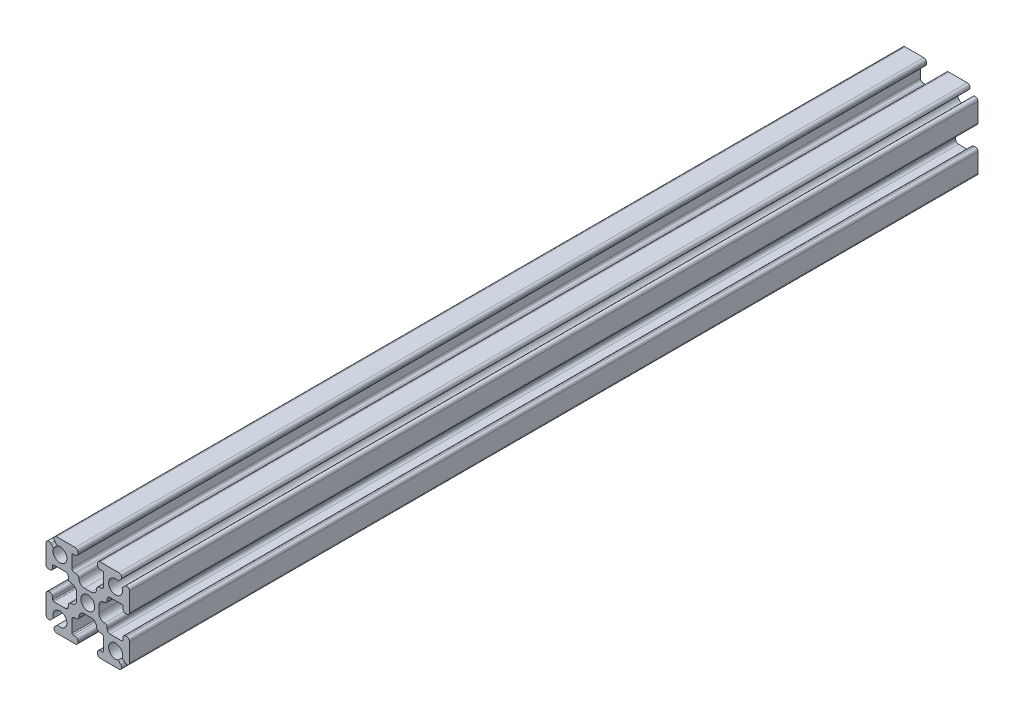
SolidWorks part; units mm, degrees
ref_plane "Front" through (0, 0, 0) normal (0, 0, 1) x (1, 0, 0)
ref_plane "Top" through (0, 0, 0) normal (0, 1, 0) x (1, 0, 0)
ref_plane "Right" through (0, 0, 0) normal (1, 0, 0) x (0, 0, -1)
sketch "Sketch1" plane through (0, 0, 0) normal (0, 0, 1) x (1, 0, 0)
  line L0 (6.6464, 5.9393) -> (6.1636, 5.4565)
  line L1 (5.4565, 6.1636) -> (5.9393, 6.6464)
  line L2 (5.5858, 7.5) -> (2.25, 7.5)
  line L3 (1.75, 7) -> (1.75, 6.8)
  line L4 (2.25, 6.3) -> (2.65, 6.3)
  line L5 (2.85, 6.1) -> (2.85, 4)
  line L6 (2.35, 3.5) -> (2.1, 3.5)
  line L7 (0.6, 2) -> (-0.6, 2)
  line L8 (-2.1, 3.5) -> (-2.35, 3.5)
  line L9 (-2.85, 4) -> (-2.85, 6.1)
  line L10 (-2.65, 6.3) -> (-2.25, 6.3)
  line L11 (-1.75, 6.8) -> (-1.75, 7)
  line L12 (-2.25, 7.5) -> (-5.5858, 7.5)
  line L13 (-5.9393, 6.6464) -> (-5.4565, 6.1636)
  line L14 (-6.1636, 5.4565) -> (-6.6464, 5.9393)
  line L15 (-7.5, 5.5858) -> (-7.5, 2.25)
  line L16 (-7, 1.75) -> (-6.8, 1.75)
  line L17 (-6.3, 2.25) -> (-6.3, 2.65)
  line L18 (-6.1, 2.85) -> (-4, 2.85)
  line L19 (-3.5, 2.35) -> (-3.5, 2.1)
  line L20 (-2, 0.6) -> (-2, -0.6)
  line L21 (-3.5, -2.1) -> (-3.5, -2.35)
  line L22 (-4, -2.85) -> (-6.1, -2.85)
  line L23 (-6.3, -2.65) -> (-6.3, -2.25)
  line L24 (-6.8, -1.75) -> (-7, -1.75)
  line L25 (-7.5, -2.25) -> (-7.5, -5.5858)
  line L26 (-6.6464, -5.9393) -> (-6.1636, -5.4565)
  line L27 (-5.4565, -6.1636) -> (-5.9393, -6.6464)
  line L28 (-5.5858, -7.5) -> (-2.25, -7.5)
  line L29 (-1.75, -7) -> (-1.75, -6.8)
  line L30 (-2.25, -6.3) -> (-2.65, -6.3)
  line L31 (-2.85, -6.1) -> (-2.85, -4)
  line L32 (-2.35, -3.5) -> (-2.1, -3.5)
  line L33 (-0.6, -2) -> (0.6, -2)
  line L34 (2.1, -3.5) -> (2.35, -3.5)
  line L35 (2.85, -4) -> (2.85, -6.1)
  line L36 (2.65, -6.3) -> (2.25, -6.3)
  line L37 (1.75, -6.8) -> (1.75, -7)
  line L38 (2.25, -7.5) -> (5.5858, -7.5)
  line L39 (5.9393, -6.6464) -> (5.4565, -6.1636)
  line L40 (6.1636, -5.4565) -> (6.6464, -5.9393)
  line L41 (7.5, -5.5858) -> (7.5, -2.25)
  line L42 (7, -1.75) -> (6.8, -1.75)
  line L43 (6.3, -2.25) -> (6.3, -2.65)
  line L44 (6.1, -2.85) -> (4, -2.85)
  line L45 (3.5, -2.35) -> (3.5, -2.1)
  line L46 (2, -0.6) -> (2, 0.6)
  line L47 (3.5, 2.1) -> (3.5, 2.35)
  line L48 (4, 2.85) -> (6.1, 2.85)
  line L49 (6.3, 2.65) -> (6.3, 2.25)
  line L50 (6.8, 1.75) -> (7, 1.75)
  line L51 (7.5, 2.25) -> (7.5, 5.5858)
  circle A0 centre (0, 0) radius 1.25
  arc A1 (6.1636, 5.4565) -> (5.4565, 6.1636) centre (5, 5) cw
  arc A2 (5.9393, 6.6464) -> (5.5858, 7.5) centre (5.5858, 7) ccw
  arc A3 (2.25, 7.5) -> (1.75, 7) centre (2.25, 7) ccw
  arc A4 (1.75, 6.8) -> (2.25, 6.3) centre (2.25, 6.8) ccw
  arc A5 (2.65, 6.3) -> (2.85, 6.1) centre (2.65, 6.1) cw
  arc A6 (2.85, 4) -> (2.35, 3.5) centre (2.35, 4) cw
  arc A7 (2.1, 3.5) -> (1.6, 3) centre (2.1, 3) ccw
  arc A8 (1.6, 3) -> (0.6, 2) centre (0.6, 3) cw
  arc A9 (-0.6, 2) -> (-1.6, 3) centre (-0.6, 3) cw
  arc A10 (-1.6, 3) -> (-2.1, 3.5) centre (-2.1, 3) ccw
  arc A11 (-2.35, 3.5) -> (-2.85, 4) centre (-2.35, 4) cw
  arc A12 (-2.85, 6.1) -> (-2.65, 6.3) centre (-2.65, 6.1) cw
  arc A13 (-2.25, 6.3) -> (-1.75, 6.8) centre (-2.25, 6.8) ccw
  arc A14 (-1.75, 7) -> (-2.25, 7.5) centre (-2.25, 7) ccw
  arc A15 (-5.5858, 7.5) -> (-5.9393, 6.6464) centre (-5.5858, 7) ccw
  arc A16 (-5.4565, 6.1636) -> (-6.1636, 5.4565) centre (-5, 5) cw
  arc A17 (-6.6464, 5.9393) -> (-7.5, 5.5858) centre (-7, 5.5858) ccw
  arc A18 (-7.5, 2.25) -> (-7, 1.75) centre (-7, 2.25) ccw
  arc A19 (-6.8, 1.75) -> (-6.3, 2.25) centre (-6.8, 2.25) ccw
  arc A20 (-6.3, 2.65) -> (-6.1, 2.85) centre (-6.1, 2.65) cw
  arc A21 (-4, 2.85) -> (-3.5, 2.35) centre (-4, 2.35) cw
  arc A22 (-3.5, 2.1) -> (-3, 1.6) centre (-3, 2.1) ccw
  arc A23 (-3, 1.6) -> (-2, 0.6) centre (-3, 0.6) cw
  arc A24 (-2, -0.6) -> (-3, -1.6) centre (-3, -0.6) cw
  arc A25 (-3, -1.6) -> (-3.5, -2.1) centre (-3, -2.1) ccw
  arc A26 (-3.5, -2.35) -> (-4, -2.85) centre (-4, -2.35) cw
  arc A27 (-6.1, -2.85) -> (-6.3, -2.65) centre (-6.1, -2.65) cw
  arc A28 (-6.3, -2.25) -> (-6.8, -1.75) centre (-6.8, -2.25) ccw
  arc A29 (-7, -1.75) -> (-7.5, -2.25) centre (-7, -2.25) ccw
  arc A30 (-7.5, -5.5858) -> (-6.6464, -5.9393) centre (-7, -5.5858) ccw
  arc A31 (-6.1636, -5.4565) -> (-5.4565, -6.1636) centre (-5, -5) cw
  arc A32 (-5.9393, -6.6464) -> (-5.5858, -7.5) centre (-5.5858, -7) ccw
  arc A33 (-2.25, -7.5) -> (-1.75, -7) centre (-2.25, -7) ccw
  arc A34 (-1.75, -6.8) -> (-2.25, -6.3) centre (-2.25, -6.8) ccw
  arc A35 (-2.65, -6.3) -> (-2.85, -6.1) centre (-2.65, -6.1) cw
  arc A36 (-2.85, -4) -> (-2.35, -3.5) centre (-2.35, -4) cw
  arc A37 (-2.1, -3.5) -> (-1.6, -3) centre (-2.1, -3) ccw
  arc A38 (-1.6, -3) -> (-0.6, -2) centre (-0.6, -3) cw
  arc A39 (0.6, -2) -> (1.6, -3) centre (0.6, -3) cw
  arc A40 (1.6, -3) -> (2.1, -3.5) centre (2.1, -3) ccw
  arc A41 (2.35, -3.5) -> (2.85, -4) centre (2.35, -4) cw
  arc A42 (2.85, -6.1) -> (2.65, -6.3) centre (2.65, -6.1) cw
  arc A43 (2.25, -6.3) -> (1.75, -6.8) centre (2.25, -6.8) ccw
  arc A44 (1.75, -7) -> (2.25, -7.5) centre (2.25, -7) ccw
  arc A45 (5.5858, -7.5) -> (5.9393, -6.6464) centre (5.5858, -7) ccw
  arc A46 (5.4565, -6.1636) -> (6.1636, -5.4565) centre (5, -5) cw
  arc A47 (6.6464, -5.9393) -> (7.5, -5.5858) centre (7, -5.5858) ccw
  arc A48 (7.5, -2.25) -> (7, -1.75) centre (7, -2.25) ccw
  arc A49 (6.8, -1.75) -> (6.3, -2.25) centre (6.8, -2.25) ccw
  arc A50 (6.3, -2.65) -> (6.1, -2.85) centre (6.1, -2.65) cw
  arc A51 (4, -2.85) -> (3.5, -2.35) centre (4, -2.35) cw
  arc A52 (3.5, -2.1) -> (3, -1.6) centre (3, -2.1) ccw
  arc A53 (3, -1.6) -> (2, -0.6) centre (3, -0.6) cw
  arc A54 (2, 0.6) -> (3, 1.6) centre (3, 0.6) cw
  arc A55 (3, 1.6) -> (3.5, 2.1) centre (3, 2.1) ccw
  arc A56 (3.5, 2.35) -> (4, 2.85) centre (4, 2.35) cw
  arc A57 (6.1, 2.85) -> (6.3, 2.65) centre (6.1, 2.65) cw
  arc A58 (6.3, 2.25) -> (6.8, 1.75) centre (6.8, 2.25) ccw
  arc A59 (7, 1.75) -> (7.5, 2.25) centre (7, 2.25) ccw
  arc A60 (7.5, 5.5858) -> (6.6464, 5.9393) centre (7, 5.5858) ccw
extrude "Boss-Extrude1" add sketch "Sketch1" along normal blind 152.4
